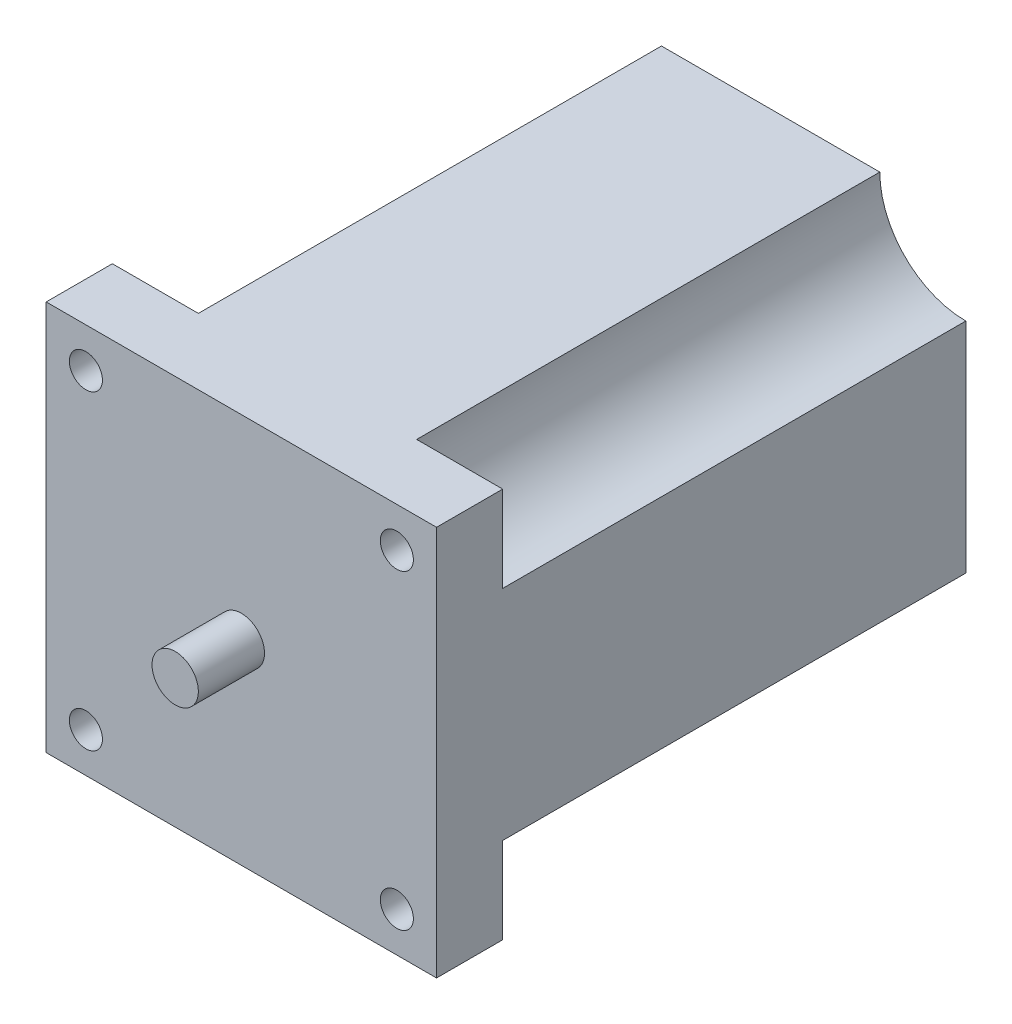
SolidWorks part; units mm, degrees
material "PVC 0.007 Plasticized"
ref_plane "Front Plane" through (0, 0, 0) normal (0, 0, 1) x (1, 0, 0)
ref_plane "Top Plane" through (0, 0, 0) normal (0, 1, 0) x (1, 0, 0)
ref_plane "Right Plane" through (0, 0, 0) normal (1, 0, 0) x (0, 0, -1)
sketch "Sketch1" plane through (0, 0, 0) normal (0, 0, 1) x (1, 0, 0)
  line L1 (-29.5, -29.5) -> (29.5, -29.5)
  line L2 (-29.5, -29.5) -> (-29.5, 29.5)
  line L3 (-29.5, 29.5) -> (29.5, 29.5)
  line L4 (29.5, -29.5) -> (29.5, 29.5)
  line L5 (-29.5, -29.5) -> (29.5, 29.5) construction
  line L6 (-29.5, 29.5) -> (29.5, -29.5) construction
  point P0 (0, 0)
  dimension "D1" = 59
  dimension "D2" = 59
extrude "Boss-Extrude1" add sketch "Sketch1" along normal blind 10
sketch "Sketch2" plane through (0, 0, 10) normal (0, 0, 1) x (1, 0, 0)
  line L0 (29.5, -29.5) -> (29.5, 29.5) construction
  line L1 (29.5, 29.5) -> (-29.5, 29.5) construction
  circle A0 centre (23.5, 23.5) radius 2.5
  circle A1 centre (23.5, -23.5) radius 2.5
  circle A2 centre (-23.5, -23.5) radius 2.5
  circle A3 centre (-23.5, 23.5) radius 2.5
  dimension "D1" = 5
  dimension "D2" = 5
  dimension "D3" = 5
  dimension "D4" = 5
  dimension "D5" = 47
  dimension "D6" = 47
  dimension "D7" = 47
  dimension "D8" = 6
  dimension "D9" = 6
extrude "Cut-Extrude2" cut sketch "Sketch2" against normal through all contours A1 | A0 | A2 | A3
sketch "Sketch4" plane through (0, 0, 10) normal (0, 0, 1) x (1, 0, 0)
  circle A0 centre (0, 0) radius 3.5
  dimension "D1" = 7
extrude "Boss-Extrude2" add sketch "Sketch4" along normal blind 10 contours A0
sketch "Sketch5" plane through (0, 0, 0) normal (0, 0, -1) x (-1, 0, 0)
  line L0 (-29.5, -29.5) -> (-29.5, 29.5) construction
  line L1 (-29.5, 29.5) -> (29.5, 29.5) construction
  line L2 (11, 0) -> (-11, 0) construction
  line L3 (0, 11) -> (0, -11) construction
  line L4 (-29.5, 16.5) -> (-29.5, -16.5)
  line L5 (-16.5, -29.5) -> (16.5, -29.5)
  line L6 (29.5, -16.5) -> (29.5, 16.5)
  line L7 (16.5, 29.5) -> (-16.5, 29.5)
  arc A0 (-29.5, 16.5) -> (-16.5, 29.5) centre (-29.5, 29.5) ccw
  arc A1 (-29.5, -16.5) -> (-16.5, -29.5) centre (-29.5, -29.5) cw
  arc A2 (29.5, -16.5) -> (16.5, -29.5) centre (29.5, -29.5) ccw
  arc A3 (29.5, 16.5) -> (16.5, 29.5) centre (29.5, 29.5) cw
extrude "Boss-Extrude3" add sketch "Sketch5" along normal blind 70
